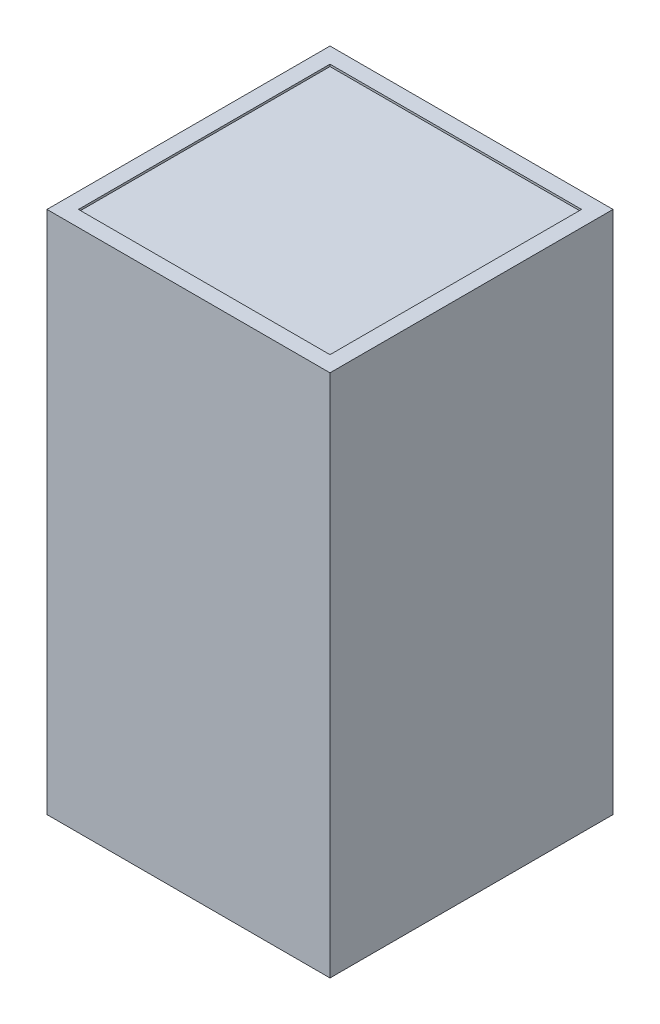
SolidWorks part; units mm, degrees
ref_plane "Front Plane" through (0, 0, 0) normal (0, 0, 1) x (1, 0, 0)
ref_plane "Top Plane" through (0, 0, 0) normal (0, 1, 0) x (1, 0, 0)
ref_plane "Right Plane" through (0, 0, 0) normal (1, 0, 0) x (0, 0, -1)
sketch "Sketch2" plane through (0, 0, 0) normal (0, 1, 0) x (1, 0, 0)
  line L1 (0, 0) -> (270, 0)
  line L2 (0, 0) -> (0, 270)
  line L3 (0, 270) -> (270, 270)
  line L4 (270, 0) -> (270, 270)
  dimension "D1" = 270
  dimension "D2" = 270
extrude "Boss-Extrude1" add sketch "Sketch2" along normal blind 500
sketch "Sketch4" plane through (0, 500, 0) normal (0, 1, 0) x (1, 0, 0)
  line L1 (0, 0) -> (270, 0)
  line L2 (0, 0) -> (0, 270)
  line L3 (0, 270) -> (270, 270)
  line L4 (270, 0) -> (270, 270)
  line L7 (270, 255) -> (255, 255)
  line L8 (255, 270) -> (255, 255)
  line L9 (255, 255) -> (15, 255)
  line L10 (255, 255) -> (255, 15)
  line L11 (255, 15) -> (15, 15)
  line L12 (15, 255) -> (15, 15)
  dimension "D1" = 15
  dimension "D2" = 15
  dimension "D3" = 240
  dimension "D4" = 240
extrude "Cut-Extrude2" cut sketch "Sketch4" against normal blind 2 contours L9 L12 L11 L10
